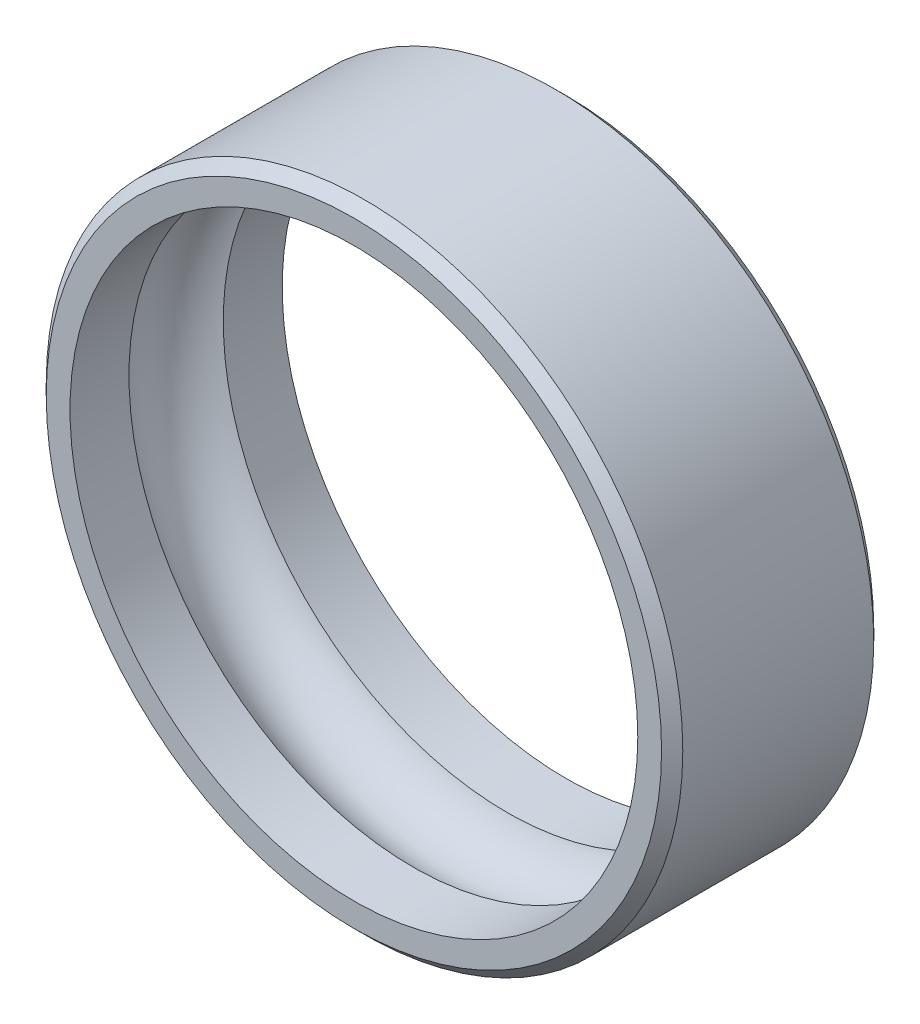
SolidWorks part; units mm, degrees
ref_plane "Front Plane" through (0, 0, 0) normal (0, 0, 1) x (1, 0, 0)
ref_plane "Top Plane" through (0, 0, 0) normal (0, 1, 0) x (1, 0, 0)
ref_plane "Right Plane" through (0, 0, 0) normal (1, 0, 0) x (0, 0, -1)
sketch "Sketch1" plane through (0, 0, 0) normal (0, 1, 0) x (1, 0, 0)
  line L0 (4.2479, 1.5875) -> (4.2479, 0.7056)
  line L1 (4.2479, -0.7056) -> (4.2479, -1.5875)
  line L2 (4.2479, -1.5875) -> (4.6038, -1.5875)
  line L3 (4.6038, -1.5875) -> (4.7625, -1.4287)
  line L4 (4.7625, -1.4287) -> (4.7625, 1.4288)
  line L5 (4.7625, 1.4288) -> (4.6038, 1.5875)
  line L6 (4.6038, 1.5875) -> (4.2479, 1.5875)
  line L7 (0, 1.5875) -> (0, -1.5875) construction
  arc A0 (4.2479, 0.7056) -> (4.2479, -0.7056) centre (3.9688, 0) cw
revolve "Revolve1" add sketch "Sketch1" angle 360 about L7
